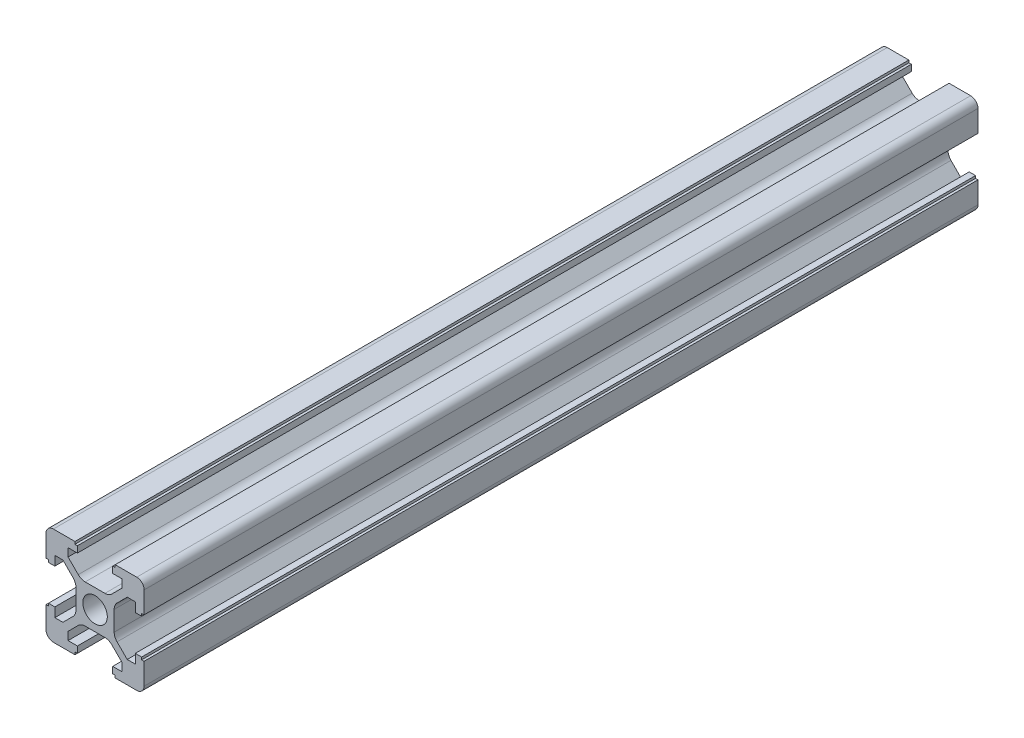
SolidWorks part; units mm, degrees
material "6063-O"
ref_plane "Front Plane" through (0, 0, 0) normal (0, 0, 1) x (1, 0, 0)
ref_plane "Top Plane" through (0, 0, 0) normal (0, 1, 0) x (1, 0, 0)
ref_plane "Right Plane" through (0, 0, 0) normal (1, 0, 0) x (0, 0, -1)
sketch "Sketch1" plane through (0, 0, 0) normal (0, 0, 1) x (1, 0, 0)
  line L0 (10, -4.1) -> (10, -8.5)
  line L1 (4.1, 10) -> (8.5, 10)
  line L2 (8.5, -10) -> (4.1, -10)
  line L3 (-8.5, -10) -> (-4.1, -10)
  line L4 (10, 8.5) -> (10, 4.1)
  line L7 (8.5, 10) -> (4.1, 10)
  line L8 (5.5, 6.5607) -> (3.4251, 4.4858)
  line L9 (8.5, 10) -> (4.1, 10)
  line L10 (3.9, 2.0109) -> (3.9, -2.0109)
  line L11 (2.0109, -3.9) -> (-2.0109, -3.9)
  line L12 (-3.9, -2.0109) -> (-3.9, 2.0109)
  line L13 (-2.0109, 3.9) -> (2.8393, 3.9)
  line L14 (2.5, 0) -> (22.2403, 0) construction
  line L15 (3.6, 9.5) -> (3.6, 8.2)
  line L16 (9.5, 3.6) -> (8.2, 3.6)
  line L17 (8.2, 3.6) -> (8.2, 5.5)
  line L18 (8.2, 5.5) -> (6.5607, 5.5)
  line L19 (10, -4.1) -> (10, -8.5)
  line L20 (4.1, 9.5) -> (3.6, 9.5)
  line L21 (4.1, 10) -> (4.1, 9.5)
  line L22 (8.5, 10) -> (4.1, 10)
  line L23 (10, 4.1) -> (9.5, 4.1)
  line L24 (9.5, 4.1) -> (9.5, 3.6)
  line L25 (5.5, 8.2) -> (5.5, 6.5607)
  line L26 (3.6, 8.2) -> (5.5, 8.2)
  line L27 (4.4858, 3.4251) -> (6.5607, 5.5)
  line L28 (10, -8.5) -> (10, -4.1)
  line L29 (6.5607, -5.5) -> (4.4858, -3.4251)
  line L30 (10, -8.5) -> (10, -4.1)
  line L31 (2.0109, -3.9) -> (-2.0109, -3.9)
  line L32 (3.9, 2.8393) -> (3.9, -2.0109)
  line L33 (9.5, -3.6) -> (8.2, -3.6)
  line L34 (3.6, -9.5) -> (3.6, -8.2)
  line L35 (3.6, -8.2) -> (5.5, -8.2)
  line L36 (5.5, -8.2) -> (5.5, -6.5607)
  line L37 (9.5, -4.1) -> (9.5, -3.6)
  line L38 (10, -4.1) -> (9.5, -4.1)
  line L39 (10, -8.5) -> (10, -4.1)
  line L40 (4.1, -10) -> (4.1, -9.5)
  line L41 (4.1, -9.5) -> (3.6, -9.5)
  line L42 (8.2, -5.5) -> (6.5607, -5.5)
  line L43 (8.2, -3.6) -> (8.2, -5.5)
  line L44 (3.4251, -4.4858) -> (5.5, -6.5607)
  line L45 (-4.1, -10) -> (-8.5, -10)
  line L46 (-10, -8.5) -> (-10, -4.1)
  line L47 (-8.5, -10) -> (-4.1, -10)
  line L48 (-5.5, -6.5607) -> (-3.4251, -4.4858)
  line L49 (-8.5, -10) -> (-4.1, -10)
  line L50 (-3.9, -2.0109) -> (-3.9, 2.0109)
  line L51 (2.0109, -3.9) -> (-2.0109, -3.9)
  line L52 (-3.6, -9.5) -> (-3.6, -8.2)
  line L53 (-9.5, -3.6) -> (-8.2, -3.6)
  line L54 (-8.2, -3.6) -> (-8.2, -5.5)
  line L55 (-8.2, -5.5) -> (-6.5607, -5.5)
  line L56 (-4.1, -9.5) -> (-3.6, -9.5)
  line L57 (-4.1, -10) -> (-4.1, -9.5)
  line L58 (-8.5, -10) -> (-4.1, -10)
  line L59 (-10, -4.1) -> (-9.5, -4.1)
  line L60 (-9.5, -4.1) -> (-9.5, -3.6)
  line L61 (-5.5, -8.2) -> (-5.5, -6.5607)
  line L62 (-3.6, -8.2) -> (-5.5, -8.2)
  line L63 (-4.4858, -3.4251) -> (-6.5607, -5.5)
  line L64 (-10, 4.1) -> (-10, 8.5)
  line L65 (-8.5, 10) -> (-4.1, 10)
  line L66 (-10, 8.5) -> (-10, 4.1)
  line L67 (-6.5607, 5.5) -> (-4.4858, 3.4251)
  line L68 (-10, 8.5) -> (-10, 4.1)
  line L69 (-2.0109, 3.9) -> (2.0109, 3.9)
  line L70 (-3.9, -2.0109) -> (-3.9, 2.0109)
  line L71 (-9.5, 3.6) -> (-8.2, 3.6)
  line L72 (-3.6, 9.5) -> (-3.6, 8.2)
  line L73 (-3.6, 8.2) -> (-5.5, 8.2)
  line L74 (-5.5, 8.2) -> (-5.5, 6.5607)
  line L75 (-9.5, 4.1) -> (-9.5, 3.6)
  line L76 (-10, 4.1) -> (-9.5, 4.1)
  line L77 (-10, 8.5) -> (-10, 4.1)
  line L78 (-4.1, 10) -> (-4.1, 9.5)
  line L79 (-4.1, 9.5) -> (-3.6, 9.5)
  line L80 (-8.2, 5.5) -> (-6.5607, 5.5)
  line L81 (-8.2, 3.6) -> (-8.2, 5.5)
  line L82 (-3.4251, 4.4858) -> (-5.5, 6.5607)
  line L83 (4.1, -10) -> (8.5, -10)
  arc A0 (2.0109, -3.9) -> (3.4251, -4.4858) centre (2.0109, -5.9) cw
  arc A1 (4.4858, -3.4251) -> (3.9, -2.0109) centre (5.9, -2.0109) cw
  arc A2 (3.9, 2.0109) -> (4.4858, 3.4251) centre (5.9, 2.0109) cw
  arc A3 (2.0109, 3.9) -> (3.4251, 4.4858) centre (2.0109, 5.9) ccw
  arc A4 (-2.0109, 3.9) -> (-3.4251, 4.4858) centre (-2.0109, 5.9) cw
  arc A5 (-4.4858, 3.4251) -> (-3.9, 2.0109) centre (-5.9, 2.0109) cw
  arc A6 (-3.4251, -4.4858) -> (-2.0109, -3.9) centre (-2.0109, -5.9) cw
  arc A7 (-3.9, -2.0109) -> (-4.4858, -3.4251) centre (-5.9, -2.0109) cw
  circle A8 centre (0, 0) radius 2.5
  arc A9 (-8.5, -10) -> (-10, -8.5) centre (-8.5, -8.5) cw
  arc A10 (-10, 8.5) -> (-8.5, 10) centre (-8.5, 8.5) cw
  arc A11 (8.5, 10) -> (10, 8.5) centre (8.5, 8.5) cw
  arc A12 (8.5, -10) -> (10, -8.5) centre (8.5, -8.5) ccw
  point P0 (0, 0)
  point P86 (0, 0)
  point P107 (10, -10)
  dimension "D3" = 2
  dimension "D5" = 5
  dimension "D2" = 1.5
  dimension "D8" = 1.5
  dimension "D6" = 4
  dimension "D7" = 6.1
  dimension "D11" = 0.5
  dimension "D12" = 0.5
extrude "Boss-Extrude2" add sketch "Sketch1" along normal blind 170
